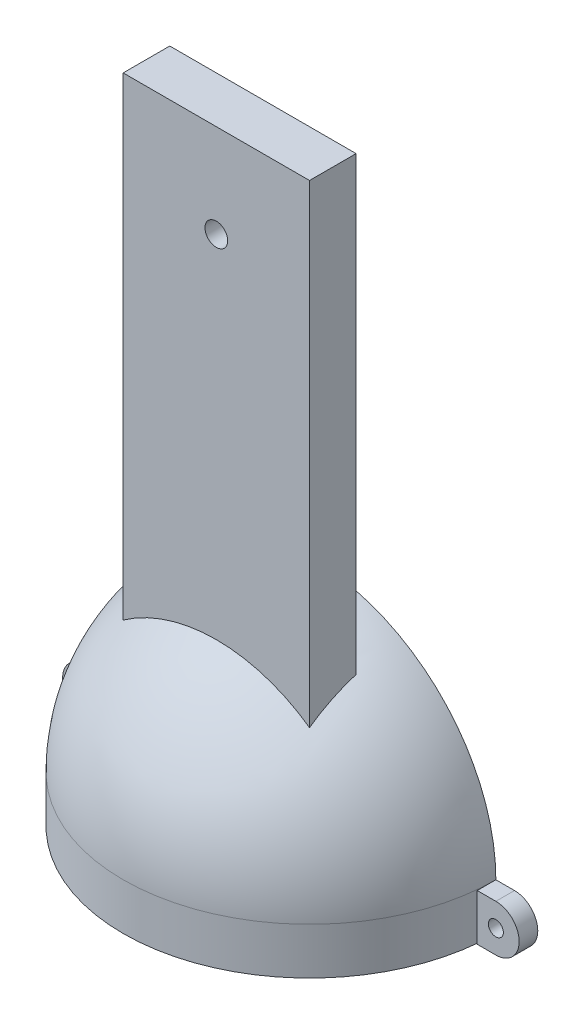
SolidWorks part; units mm, degrees
ref_plane "Front Plane" through (0, 0, 0) normal (0, 0, 1) x (1, 0, 0)
ref_plane "Top Plane" through (0, 0, 0) normal (0, 1, 0) x (1, 0, 0)
ref_plane "Right Plane" through (0, 0, 0) normal (1, 0, 0) x (0, 0, -1)
sketch "Sketch1" plane through (0, 0, 0) normal (0, 0, 1) x (1, 0, 0)
  line L0 (-15, 0) -> (-10, 0)
  line L2 (-20, 0) -> (-20, -10)
  line L3 (-20, -10) -> (-10, -10)
  line L4 (20, 0) -> (20, -10)
  line L6 (-10, -10) -> (-10, 0)
  line L8 (10, -10) -> (10, 0)
  line L9 (10, 0) -> (15, 0)
  line L10 (10, -10) -> (20, -10)
  line L11 (-20, 0) -> (20, 0)
  arc A0 (20, 0) -> (-20, 0) centre (0, 0) ccw
  arc A3 (15, 0) -> (-15, 0) centre (0, 0) ccw
  dimension "D1" = 10
  dimension "D2" = 20
  dimension "D4" = 10
  dimension "D6" = 15
  dimension "D3" = 10
  dimension "D5" = 10
revolve "Revolve2" add sketch "Sketch1" angle 90 about L9
sketch "Sketch3" plane through (0, 0, 0) normal (0, -1, 0) x (1, 0, 0)
  line L0 (-15, 0) -> (15, 0) construction
  line L1 (-20, 0) -> (-10, 0)
  line L2 (10, 0) -> (20, 0)
  arc A0 (10, 0) -> (-10, 0) centre (0, 0) ccw
  arc A1 (20, 0) -> (-20, 0) centre (0, 0) ccw
  dimension "D1" = 10
extrude "Boss-Extrude2" add sketch "Sketch3" along normal blind 5
sketch "Sketch5" plane through (0, 0, 0) normal (0, 0, -1) x (-1, 0, 0)
  line L2 (0, 11) -> (0, -11) construction
  line L3 (-22, 0) -> (-20, 0)
  line L5 (-22, -5) -> (-20, -5)
  line L6 (-20, 0) -> (-20, -5)
  line L7 (22, -5) -> (20, -5)
  line L8 (22, 0) -> (20, 0)
  line L9 (20, -5) -> (20, 0)
  arc A0 (-22, 0) -> (-22, -5) centre (-22, -2.5) ccw
  arc A1 (22, 0) -> (22, -5) centre (22, -2.5) cw
  dimension "D1" = 2.5
extrude "Boss-Extrude3" add sketch "Sketch5" against normal blind 2 separate body
sketch "Sketch10" plane through (0, 0, 0) normal (0, 1, 0) x (1, 0, 0)
  line L0 (10, 0) -> (15, 0) construction
  line L1 (10, -5) -> (-10, -5)
  line L2 (10, -5) -> (10, -10)
  line L3 (10, -10) -> (-10, -10)
  line L4 (-10, -5) -> (-10, -10)
  dimension "D1" = 20
  dimension "D2" = 5
  dimension "D3" = 5
  dimension "D4" = 10
extrude "Boss-Extrude4" add sketch "Sketch10" along normal blind 50 and the other way up to body from offset 15 separate body
sketch "Sketch11" plane through (0, 0, 5) normal (0, 0, -1) x (-1, 0, 0)
  line L0 (-10, 65) -> (10, 65) construction
  circle A0 centre (0, 55) radius 5
  dimension "D1" = 10
  dimension "D2" = 10
extrude "Boss-Extrude6" add sketch "Sketch11" along normal blind 5
ref_plane "Plane1" through (0, 0, 0) normal (0, 0, -1) x (-1, 0, 0)
sketch "Sketch12" plane through (0, 0, 0) normal (0, 0, -1) x (-1, 0, 0)
  circle A0 centre (0, 55) radius 1.22
  circle A1 centre (-22, -2.5) radius 0.805
  circle A2 centre (22, -2.5) radius 0.805
  dimension "D1" = 1.61
  dimension "D2" = 1.61
  dimension "D3" = 2.44
extrude "Cut-Extrude1" cut sketch "Sketch12" against normal blind 10
